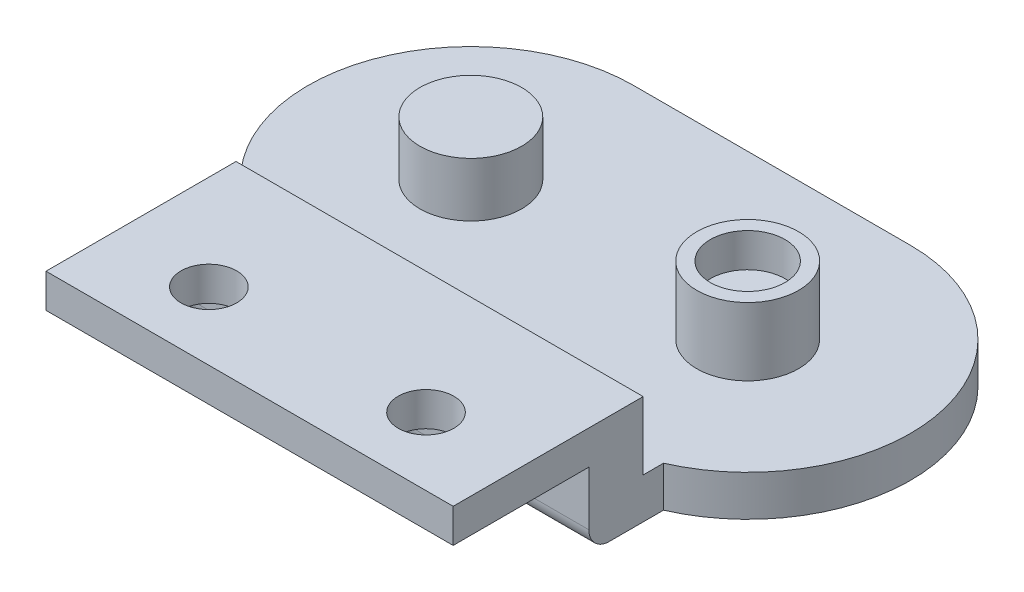
SolidWorks part; units mm, degrees
ref_plane "Plan de face" through (0, 0, 0) normal (0, 0, 1) x (1, 0, 0)
ref_plane "Plan de dessus" through (0, 0, 0) normal (0, 1, 0) x (1, 0, 0)
ref_plane "Plan de droite" through (0, 0, 0) normal (1, 0, 0) x (0, 0, -1)
sketch "Esquisse1" plane through (0, 0, 0) normal (0, 1, 0) x (1, 0, 0)
  line L0 (-16.5, 0) -> (17.7857, 0) construction
  line L1 (0, 17.5357) -> (0, -17.8929) construction
  line L2 (-17.3742, 12) -> (19.2232, 12) construction
  line L5 (-15, 16.3741) -> (-15, -18.4071) construction
  line L6 (-10.2, 12) -> (10.2, 12)
  line L7 (-15, -10.9982) -> (-15, -16.5)
  line L8 (-15, -16.5) -> (15, -16.5)
  line L9 (15, -10.9982) -> (15, -16.5)
  line L10 (-24.0817, -12) -> (26.7733, -12) construction
  arc A2 (-10.2, 12) -> (-15, -10.9982) centre (-10.2, 0) ccw
  arc A3 (10.2, 12) -> (15, -10.9982) centre (10.2, 0) cw
  point P16 (0, -16.5)
  point P19 (0, 12)
  dimension "D1" = 10.2
  dimension "D2" = 12
  dimension "D3" = 15
  dimension "D4" = 12
  dimension "D5" = 4.5
extrude "Boss.-Extru.1" add sketch "Esquisse1" along normal blind 3
sketch "Esquisse2" plane through (0, 3, 0) normal (0, 1, 0) x (1, 0, 0)
  line L2 (-15, -10.9982) -> (-15, -16.5)
  line L3 (-15, -10.9982) -> (-15, -16.5)
  line L8 (-15, -16.5) -> (15, -16.5)
  line L9 (-15, -16.5) -> (15, -16.5)
  line L10 (15, -16.5) -> (15, -10.9982)
  line L11 (15, -16.5) -> (15, -10.9982)
  line L12 (10.2, 12) -> (-10.2, 12)
  line L13 (10.2, 12) -> (-10.2, 12)
  circle A0 centre (-10.2, 0) radius 3.75
  circle A1 centre (10.2, 0) radius 3.75
  arc A2 (-10.2, 12) -> (-15, -10.9982) centre (-10.2, 0) ccw
  arc A3 (-10.2, 12) -> (-15, -10.9982) centre (-10.2, 0) ccw
  arc A8 (15, -10.9982) -> (10.2, 12) centre (10.2, 0) ccw
  arc A9 (15, -10.9982) -> (10.2, 12) centre (10.2, 0) ccw
  dimension "D2" = 7.5
  dimension "D3" = 7.5
  dimension "D1" = 0
extrude "Boss.-Extru.2" add sketch "Esquisse2" along normal blind 5 contours A1
sketch "Esquisse4" plane through (0, 3, 0) normal (0, 1, 0) x (1, 0, 0)
  line L0 (-15, -12.5) -> (15, -12.5)
  line L1 (-15, -10.9982) -> (-15, -16.5) construction
  line L2 (15, -16.5) -> (15, -10.9982) construction
  line L3 (-15, -16.5) -> (15, -16.5) construction
  line L8 (-15, -10.9982) -> (-15, -16.5)
  line L9 (-15, -16.5) -> (15, -16.5)
  line L10 (15, -16.5) -> (15, -10.9982)
  line L11 (10.2, 12) -> (-10.2, 12)
  line L12 (-15, -10.9982) -> (-15, -16.5)
  line L13 (-15, -16.5) -> (15, -16.5)
  line L14 (15, -16.5) -> (15, -10.9982)
  line L15 (10.2, 12) -> (-10.2, 12)
  arc A2 (-10.2, 12) -> (-15, -10.9982) centre (-10.2, 0) ccw
  arc A3 (15, -10.9982) -> (10.2, 12) centre (10.2, 0) ccw
  arc A4 (-10.2, 12) -> (-15, -10.9982) centre (-10.2, 0) ccw
  arc A5 (15, -10.9982) -> (10.2, 12) centre (10.2, 0) ccw
  line M5 (-15, -10.9982) -> (-15, -16.5)
  line M6 (-15, -16.5) -> (15, -16.5)
  line M7 (15, -16.5) -> (15, -10.9982)
  dimension "D1" = 4
  dimension "D2" = 0
extrude "Boss.-Extru.3" add sketch "Esquisse4" along normal blind 5 contours L0 M5 M6 M7
sketch "Esquisse5" plane through (0, 0, 16.5) normal (0, 0, 1) x (1, 0, 0)
  line L0 (-15, 5.5) -> (15, 5.5)
  line L4 (-15, 0) -> (15, 0)
  line L5 (15, 0) -> (15, 8)
  line L6 (15, 8) -> (-15, 8)
  line L7 (-15, 8) -> (-15, 0)
  line L8 (-15, 0) -> (15, 0)
  line L9 (15, 0) -> (15, 8)
  line L10 (15, 8) -> (-15, 8)
  line L11 (-15, 8) -> (-15, 0)
  line M7 (15, 0) -> (15, 8)
  line M8 (15, 8) -> (-15, 8)
  line M9 (-15, 8) -> (-15, 0)
  dimension "D2" = 2.5
  dimension "D1" = 0
extrude "Boss.-Extru.4" add sketch "Esquisse5" along normal blind 10 contours L0 M9 M7 M8
sketch "Esquisse6" plane through (0, 8, 0) normal (0, 1, 0) x (1, 0, 0)
  line L0 (0, -27.0696) -> (0, 14.1578) construction
  line L1 (-18.2509, -21.5) -> (23.7913, -21.5) construction
  line L4 (15, -16.5) -> (-15, -16.5)
  line L5 (15, -26.5) -> (15, -16.5)
  line L6 (-15, -26.5) -> (15, -26.5)
  line L7 (-15, -16.5) -> (-15, -26.5)
  line L8 (15, -16.5) -> (-15, -16.5)
  line L9 (15, -26.5) -> (15, -16.5)
  line L10 (-15, -26.5) -> (15, -26.5)
  line L11 (-15, -16.5) -> (-15, -26.5)
  circle A0 centre (-8, -21.5) radius 2.05
  circle A1 centre (8, -21.5) radius 2.05
  dimension "D2" = 4.1
  dimension "D3" = 8
  dimension "D1" = 0
extrude "Enlèv. mat.-Extru.3" cut sketch "Esquisse6" against normal blind 10 contours A1 | A0
sketch "Esquisse7" plane through (0, 8, 0) normal (0, 1, 0) x (1, 0, 0)
  circle A0 centre (10.2, 0) radius 2.75
  circle A1 centre (10.2, 0) radius 3.75
  circle A2 centre (10.2, 0) radius 3.75
  dimension "D2" = 5.5
  dimension "D1" = 0
extrude "Enlèv. mat.-Extru.4" cut sketch "Esquisse7" against normal blind 2.5 contours A0
sketch "Esquisse8" plane through (0, 3, 0) normal (0, 1, 0) x (1, 0, 0)
  line L4 (-15, -12.5) -> (15, -12.5)
  line L5 (15, -12.5) -> (15, -10.9982)
  line L6 (10.2, 12) -> (-10.2, 12)
  line L7 (-15, -10.9982) -> (-15, -12.5)
  line L8 (-15, -12.5) -> (15, -12.5)
  line L9 (15, -12.5) -> (15, -10.9982)
  line L10 (10.2, 12) -> (-10.2, 12)
  line L11 (-15, -10.9982) -> (-15, -12.5)
  circle A0 centre (-10.2, 0) radius 3.75
  arc A2 (15, -10.9982) -> (10.2, 12) centre (10.2, 0) ccw
  arc A3 (-10.2, 12) -> (-15, -10.9982) centre (-10.2, 0) ccw
  arc A4 (15, -10.9982) -> (10.2, 12) centre (10.2, 0) ccw
  arc A5 (-10.2, 12) -> (-15, -10.9982) centre (-10.2, 0) ccw
  dimension "D2" = 7.5
  dimension "D1" = 0
extrude "Boss.-Extru.5" add sketch "Esquisse8" along normal blind 4 contours A0
fillet "Congé1" radius 1.5 1 edges at (0, 0, 16.5)
